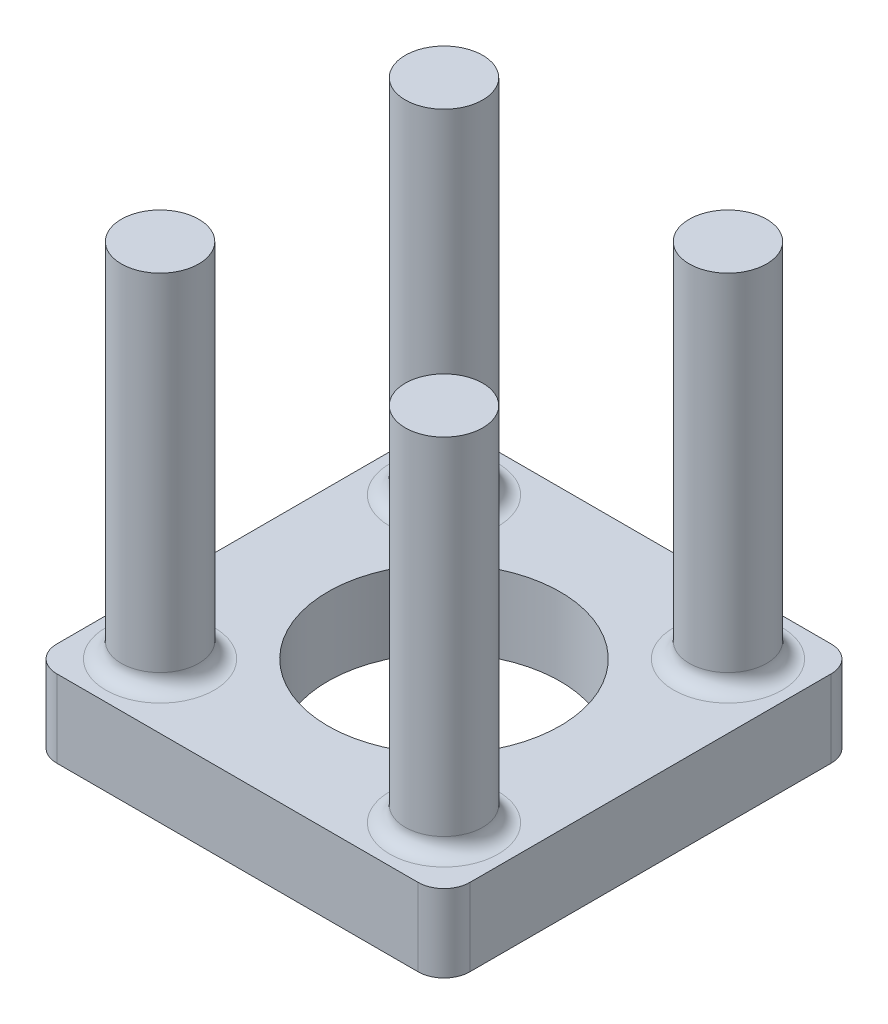
SolidWorks part; units mm, degrees
ref_plane "前基準面" through (0, 0, 0) normal (0, 0, 1) x (1, 0, 0)
ref_plane "上基準面" through (0, 0, 0) normal (0, 1, 0) x (1, 0, 0)
ref_plane "右基準面" through (0, 0, 0) normal (1, 0, 0) x (0, 0, -1)
sketch "草圖1" plane through (0, 0, 0) normal (0, 1, 0) x (1, 0, 0)
  line L1 (-28.9756, 18.5488) -> (51.0244, 18.5488)
  line L2 (-28.9756, 18.5488) -> (-28.9756, -61.4512)
  line L3 (-28.9756, -61.4512) -> (51.0244, -61.4512)
  line L4 (51.0244, 18.5488) -> (51.0244, -61.4512)
  circle A0 centre (11.0244, -21.4512) radius 22.5
  dimension "D1" = 45
  dimension "D2" = 80
  dimension "D3" = 40
  dimension "D4" = 40
  dimension "D5" = 80
extrude "填料-伸長1" add sketch "草圖1" along normal blind 15
fillet "圓角1" radius 5 4 edges at (-28.9756, 7.5, -18.5488) (-28.9756, 7.5, 61.4512) (51.0244, 7.5, 61.4512) (51.0244, 7.5, -18.5488)
sketch "草圖2" plane through (0, 15, 0) normal (0, 1, 0) x (1, 0, 0)
  line L0 (-28.9756, 13.5488) -> (-28.9756, -56.4512) construction
  line L1 (46.0244, 18.5488) -> (-23.9756, 18.5488) construction
  line L2 (51.0244, -56.4512) -> (51.0244, 13.5488) construction
  line L3 (-23.9756, -61.4512) -> (46.0244, -61.4512) construction
  circle A0 centre (-16.4756, 6.0488) radius 7.5
  circle A1 centre (38.5244, 6.0488) radius 7.5
  circle A2 centre (38.5244, -48.9512) radius 7.5
  circle A3 centre (-16.4756, -48.9512) radius 7.5
  dimension "D1" = 15
  dimension "D2" = 15
  dimension "D3" = 15
  dimension "D4" = 15
  dimension "D6" = 12.5
  dimension "D7" = 12.5
  dimension "D8" = 12.5
  dimension "D9" = 12.5
  dimension "D10" = 12.5
  dimension "D11" = 12.5
  dimension "D12" = 12.5
  dimension "D5" = 12.5
extrude "填料-伸長2" add sketch "草圖2" along normal blind 70
fillet "圓角2" radius 3 4 edges at (-16.4756, 15, 56.4512) (38.5244, 15, 56.4512) (38.5244, 15, 1.4512) (-16.4756, 15, 1.4512)
